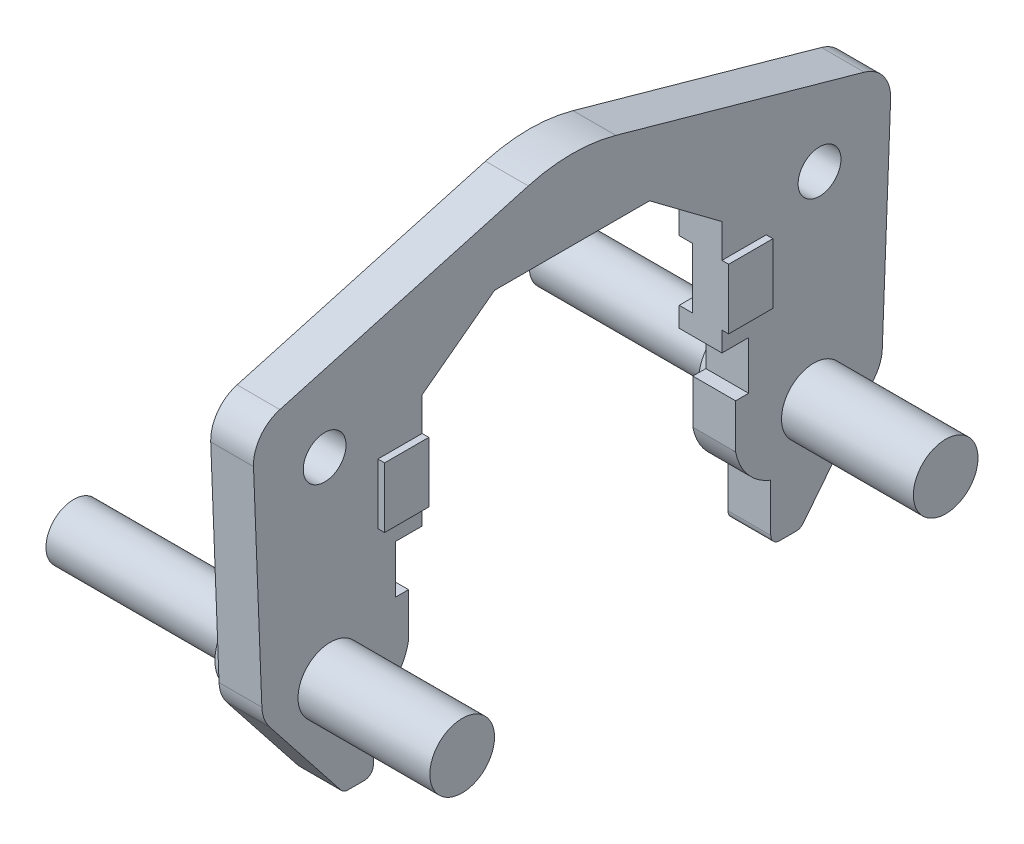
SolidWorks part; units mm, degrees
other "Markup1"
sketch "Sketch11" plane through (-4.4196, 30.4284, 44.8044) normal (-0.191, 0.0171, 0.9814) x (0.9816, 0.001, 0.191)
ref_plane "Front Plane" through (0, 0, 0) normal (0, 0, 1) x (1, 0, 0)
ref_plane "Top Plane" through (0, 0, 0) normal (0, 1, 0) x (1, 0, 0)
ref_plane "Right Plane" through (0, 0, 0) normal (1, 0, 0) x (0, 0, -1)
sketch "Sketch2" plane through (0, 0, 0) normal (1, 0, 0) x (0, 0, -1)
  line L0 (0, -6.8175) -> (0, 5.2838) construction
  line L1 (-31.5156, -31.3055) -> (-29.21, -31.3055)
  line L7 (-10.8966, 19.2405) -> (10.8966, 19.2405)
  line L8 (10.8966, 19.2405) -> (21.082, 11.6205)
  line L9 (21.082, 11.6205) -> (21.082, -4.3815)
  line L10 (21.082, -4.3815) -> (24.8285, -4.3815)
  line L11 (24.8285, -4.3815) -> (24.8285, -11.1633)
  line L12 (24.8285, -11.1633) -> (22.9981, -11.1633)
  line L13 (22.9981, -11.1633) -> (22.9981, -17.3863)
  line L14 (27.94, -30.0355) -> (27.94, -23.3045)
  line L15 (29.21, -31.3055) -> (31.5156, -31.3055)
  line L16 (32.5124, -30.8224) -> (42.537, -18.1246)
  line L17 (6.1568, 29.5837) -> (41.0925, 19.8135)
  line L18 (43.6259, -15.1762) -> (44.8004, 14.7218)
  line L19 (-43.6259, -15.1762) -> (-44.8004, 14.7218)
  line L20 (-32.5124, -30.8224) -> (-42.537, -18.1246)
  line L21 (-27.94, -30.0355) -> (-27.94, -23.3045)
  line L22 (-22.9981, -11.1633) -> (-22.9981, -17.3863)
  line L23 (-24.8285, -11.1633) -> (-22.9981, -11.1633)
  line L24 (-24.8285, -4.3815) -> (-24.8285, -11.1633)
  line L25 (-21.082, -4.3815) -> (-24.8285, -4.3815)
  line L26 (-21.082, 11.6205) -> (-21.082, -4.3815)
  line L27 (-10.8966, 19.2405) -> (-21.082, 11.6205)
  line L28 (-6.1568, 29.5837) -> (-41.0925, 19.8135)
  line L29 (27.94, -31.3055) -> (32.131, -31.3055)
  arc A0 (27.94, -23.3045) -> (22.9981, -17.3863) centre (30.7808, -15.91) cw
  arc A1 (-27.94, -23.3045) -> (-22.9981, -17.3863) centre (-30.7808, -15.91) ccw
  arc A2 (6.1568, 29.5837) -> (-6.1568, 29.5837) centre (0, 7.5684) ccw
  arc A3 (41.0925, 19.8135) -> (44.8004, 14.7218) centre (39.7244, 14.9212) cw
  arc A4 (-44.8004, 14.7218) -> (-41.0925, 19.8135) centre (-39.7244, 14.9212) cw
  arc A5 (-43.6259, -15.1762) -> (-42.537, -18.1246) centre (-38.5498, -14.9768) ccw
  arc A6 (42.537, -18.1246) -> (43.6259, -15.1762) centre (38.5498, -14.9768) ccw
  arc A7 (31.5156, -31.3055) -> (32.5124, -30.8224) centre (31.5156, -30.0355) ccw
  arc A8 (-32.5124, -30.8224) -> (-31.5156, -31.3055) centre (-31.5156, -30.0355) ccw
  arc A9 (27.94, -30.0355) -> (29.21, -31.3055) centre (29.21, -30.0355) ccw
  arc A10 (-27.94, -30.0355) -> (-29.21, -31.3055) centre (-29.21, -30.0355) cw
  circle A13 centre (34.798, 10.8585) radius 3.0099
  circle A14 centre (-34.798, 10.8585) radius 3.0099
  point P0 (0, 0)
  point P7 (44.958, 18.7325)
  point P36 (0, 19.2405)
  point P41 (43.561, -16.8275)
  dimension "D18" = 7.9214
  dimension "D2" = 22.86
  dimension "D4" = 5.08
  dimension "D7" = 5.08
  dimension "D9" = 1.27
  dimension "D12" = 1.27
  dimension "D15" = 69.596
  dimension "D20" = 6.0198
  dimension "D32" = 6.0198
  dimension "D42" = 7.9214
  dimension "D47" = 5.9523
  dimension "D3" = 10.8966
  dimension "D5" = 7.62
  dimension "D6" = 16.002
  dimension "D8" = 6.7818
  dimension "D10" = 6.223
  dimension "D11" = 8.001
  dimension "D13" = 4.191
  dimension "D14" = 14.478
  dimension "D16" = 35.56
  dimension "D17" = 34.798
  dimension "D19" = 42.164
  dimension "D21" = 42.164
  dimension "D22" = 21.082
  dimension "D23" = 24.8285
  dimension "D24" = 27.94
  dimension "D25" = 11.6721
  dimension "D26" = 29.898
  dimension "D27" = 2.25
  dimension "D28" = 22.9981
  dimension "D29" = 24.8285
  dimension "D30" = 4.3815
  dimension "D31" = 12.7203
  dimension "D33" = 22.9981
  dimension "D34" = 4.3815
  dimension "D35" = 6.7818
  dimension "D36" = 6.731
  dimension "D37" = 2.25
  dimension "D38" = 21.177
  dimension "D39" = 53.199
  dimension "D40" = 21.177
  dimension "D41" = 90
  dimension "D43" = 38.29
  dimension "D44" = 16.178
  dimension "D45" = 27.94
  dimension "D46" = 9.8431
extrude "Boss-Extrude1" add sketch "Sketch2" along normal blind 6.0198 contours L7 L0 A2 L28 A4 L19 A5 L20 A8 L1 A10 L21 A1 L22 L23 L24 L25 L26 L27 A14 | L0 L7 L8 L9 L10 L11 L12 L13 A0 L14 A9 L15 A7 L16 A6 L18 A3 L17 A2 A13
sketch "Sketch3" plane through (6.0198, 0, 0) normal (1, 0, 0) x (0, 0, -1)
  line L0 (21.082, 11.6205) -> (21.082, -4.3815) construction
  line L1 (21.082, 6.8961) -> (27.305, 6.8961)
  line L2 (21.082, 6.8961) -> (21.082, -1.5875)
  line L3 (21.082, -1.5875) -> (27.305, -1.5875)
  line L4 (27.305, 6.8961) -> (27.305, -1.5875)
  line L5 (-21.082, 11.6205) -> (-21.082, -4.3815) construction
  line L6 (-21.082, 6.8961) -> (-27.305, 6.8961)
  line L7 (-21.082, 6.8961) -> (-21.082, -1.5875)
  line L8 (-21.082, -1.5875) -> (-27.305, -1.5875)
  line L9 (-27.305, 6.8961) -> (-27.305, -1.5875)
  line L10 (-21.082, -4.3815) -> (-24.8285, -4.3815) construction
  line L11 (21.082, -4.3815) -> (24.8285, -4.3815) construction
  line L12 (29.21, -31.3055) -> (31.5156, -31.3055) construction
  circle A0 centre (33.9979, -16.6162) radius 4.5466
  circle A1 centre (-33.9979, -16.6162) radius 4.5466
  point P16 (-24.1935, -1.5875)
  dimension "D7" = 9.0932
  dimension "D8" = 9.0932
  dimension "D1" = 6.223
  dimension "D2" = 8.4836
  dimension "D3" = 2.794
  dimension "D4" = 6.223
  dimension "D5" = 2.794
  dimension "D6" = 8.4836
  dimension "D9" = 67.9958
  dimension "D10" = 33.9979
  dimension "D11" = 14.6893
extrude "Boss-Extrude2" add sketch "Sketch3" along normal blind 0.9398 contours L7 L6 L9 L8 | A1 | L2 L1 L4 L3 | A0
sketch "Sketch4" plane through (6.9596, 0, 0) normal (1, 0, 0) x (0, 0, -1)
  circle A0 centre (-33.9979, -16.6162) radius 4.5466
  circle A1 centre (33.9979, -16.6162) radius 4.5466
extrude "Boss-Extrude3" add sketch "Sketch4" along normal blind 17.6022
sketch "Sketch5" plane through (0, 0, 0) normal (-1, 0, 0) x (0, 0, 1)
  line L1 (-21.082, -1.5875) -> (-27.305, -1.5875)
  line L2 (-21.082, -1.5875) -> (-21.082, 6.8961)
  line L3 (-21.082, 6.8961) -> (-27.305, 6.8961)
  line L4 (-27.305, -1.5875) -> (-27.305, 6.8961)
  line L5 (21.082, -1.5875) -> (27.305, -1.5875)
  line L6 (21.082, -1.5875) -> (21.082, 6.8961)
  line L7 (21.082, 6.8961) -> (27.305, 6.8961)
  line L8 (27.305, -1.5875) -> (27.305, 6.8961)
  circle A0 centre (-33.9979, -16.6162) radius 4.5466
  circle A1 centre (33.9979, -16.6162) radius 4.5466
extrude "Cut-Extrude1" cut sketch "Sketch5" against normal blind 1.8542 contours L2 L1 L4 L3 | L6 L5 L8 L7
sketch "Sketch6" plane through (0, 0, 0) normal (-1, 0, 0) x (0, 0, 1)
  circle A0 centre (33.9979, -16.6162) radius 5.969
  circle A1 centre (-33.9979, -16.6162) radius 5.969
  dimension "D1" = 11.938
  dimension "D2" = 11.938
extrude "Boss-Extrude4" add sketch "Sketch6" along normal blind 1.8542
sketch "Sketch8" plane through (-1.8542, 0, 0) normal (-1, 0, 0) x (0, 0, 1)
  circle A0 centre (33.9979, -16.6162) radius 5.8801
  dimension "D1" = 11.7602
sketch "Sketch9" plane through (-1.8542, 0, 0) normal (-1, 0, 0) x (0, 0, 1)
  line L0 (0, -14.5288) -> (0, 14.5288) construction
  circle A0 centre (33.9979, -16.6162) radius 6.985
  circle A1 centre (-33.9979, -16.6162) radius 6.985
  dimension "D1" = 13.97
extrude "Boss-Extrude6" add sketch "Sketch9" along normal blind 2.5654
draft "Draft2" type of draft neutral plane draft angle 25 faces to draft 1 face at (-4.4196, -16.6162, -40.9829) neutral plane through (-1.8542, -16.6162, -33.9979) neutral plane normal (1, 0, 0) reverse direction yes parameters "D1"=25
draft "Draft3" type of draft neutral plane draft angle 25 faces to draft 1 face at (-4.4196, -16.6162, 40.9829) neutral plane through (-1.8542, -16.6162, 33.9979) neutral plane normal (1, 0, 0) reverse direction yes parameters "D1"=25
sketch "Sketch12" plane through (-4.4196, 0, 0) normal (-1, 0, 0) x (0, 0, 1)
  line L0 (0, -15.9398) -> (0, 15.9398) construction
  circle A0 centre (-33.9979, -16.6162) radius 3.8989
  circle A1 centre (33.9979, -16.6162) radius 3.8989
  dimension "D1" = 7.7978
extrude "Boss-Extrude7" add sketch "Sketch12" along normal blind 25.654
